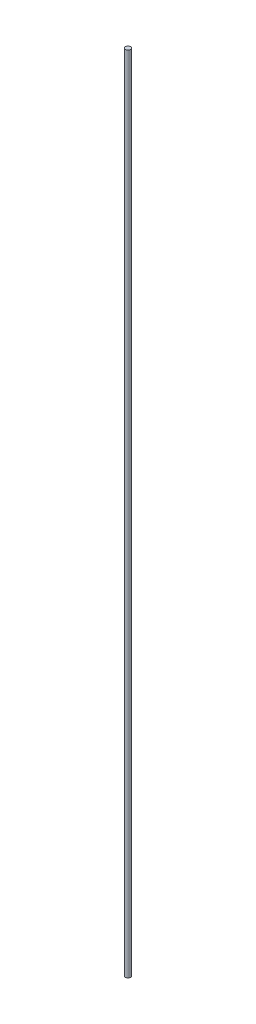
SolidWorks part; units mm, degrees
ref_plane "Front Plane" through (0, 0, 0) normal (0, 0, 1) x (1, 0, 0)
ref_plane "Top Plane" through (0, 0, 0) normal (0, 1, 0) x (1, 0, 0)
ref_plane "Right Plane" through (0, 0, 0) normal (1, 0, 0) x (0, 0, -1)
sketch "Sketch1" plane through (0, 0, 0) normal (0, 0, 1) x (1, 0, 0)
  line L0 (0, 0) -> (0, 1999.996)
  dimension "D1" = 1999.996
sweep "Sweep1" add path "Sketch1" circular profile diameter 12.7 parameters "D3"=12.7
